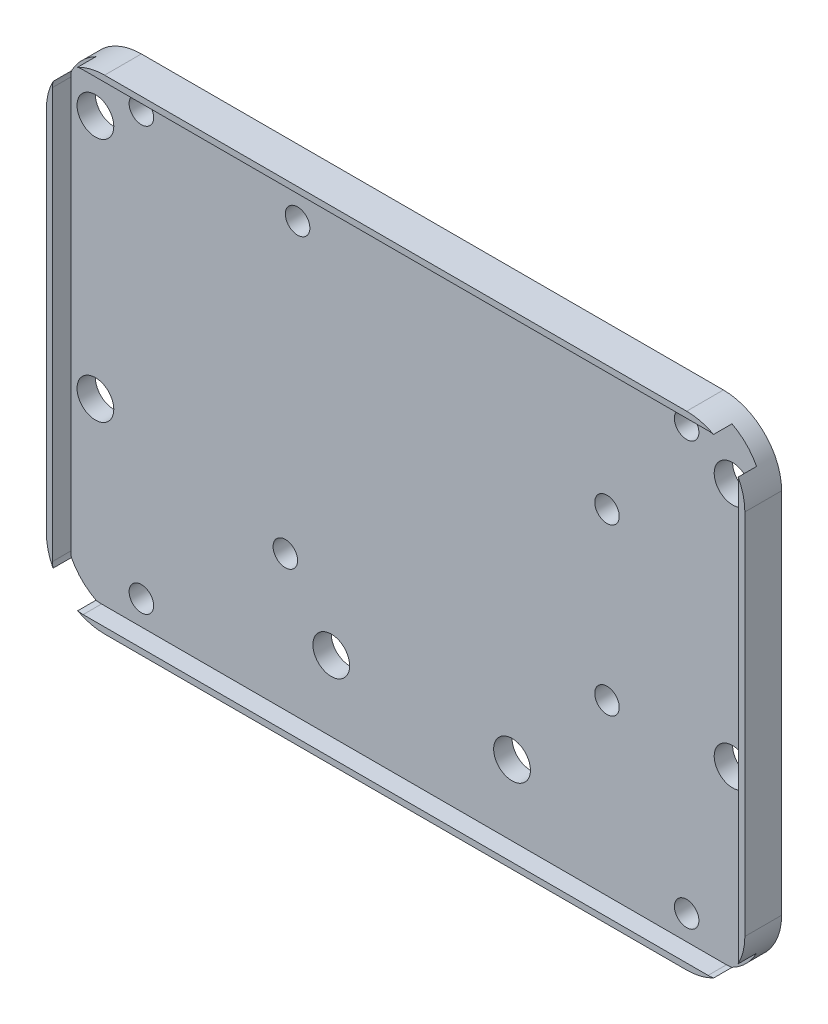
SolidWorks part; units mm, degrees
ref_plane "Plan de face" through (0, 0, 0) normal (0, 0, 1) x (1, 0, 0)
ref_plane "Plan de dessus" through (0, 0, 0) normal (0, 1, 0) x (1, 0, 0)
ref_plane "Plan de droite" through (0, 0, 0) normal (1, 0, 0) x (0, 0, -1)
sketch "Esquisse1" plane through (0, 0, 0) normal (0, 0, 1) x (1, 0, 0)
  line L1 (7.9933, 75.3455) -> (102.9933, 75.3455)
  line L2 (-1.5067, 65.8455) -> (-1.5067, 5.8455)
  line L3 (7.9933, -3.6545) -> (102.9933, -3.6545)
  line L4 (112.4933, 65.8455) -> (112.4933, 5.8455)
  circle A0 centre (107.4933, 65.8455) radius 3
  circle A1 centre (107.4933, 25.8455) radius 3
  circle A2 centre (3.4933, 65.8455) radius 3
  circle A3 centre (3.4933, 25.8455) radius 3
  arc A4 (-1.5067, 5.8455) -> (7.9933, -3.6545) centre (7.9933, 5.8455) ccw
  arc A5 (102.9933, -3.6545) -> (112.4933, 5.8455) centre (102.9933, 5.8455) ccw
  arc A6 (102.9933, 75.3455) -> (112.4933, 65.8455) centre (102.9933, 65.8455) cw
  arc A7 (7.9933, 75.3455) -> (-1.5067, 65.8455) centre (7.9933, 65.8455) ccw
  point P18 (112.4933, 75.3455)
  point P21 (-1.5067, 75.3455)
  dimension "D1" = 40
  dimension "D4" = 40
  dimension "D8" = 6
  dimension "D9" = 6
  dimension "D10" = 6
  dimension "D11" = 6
  dimension "D2" = 79
  dimension "D3" = 114
  dimension "D5" = 104
  dimension "D6" = 104
  dimension "D7" = 5
  dimension "D12" = 9.5
extrude "Boss.-Extru.3" add sketch "Esquisse1" along normal blind 6
sketch "Esquisse3" plane through (0, 0, 6) normal (0, 0, 1) x (1, 0, 0)
  line L0 (-1.5067, 65.8455) -> (-1.5067, 5.8455) construction
  line L1 (4.4933, 74.3455) -> (106.4933, 74.3455)
  line L2 (-0.5067, 69.3455) -> (-0.5067, 2.3455)
  line L3 (4.4933, -2.6545) -> (106.4933, -2.6545)
  line L4 (111.4933, 69.3455) -> (111.4933, 2.3455)
  line L5 (102.9933, 75.3455) -> (7.9933, 75.3455) construction
  line L6 (7.9933, -3.6545) -> (102.9933, -3.6545) construction
  line L7 (112.4933, 5.8455) -> (112.4933, 65.8455) construction
  arc A0 (-0.5067, 2.3455) -> (4.4933, -2.6545) centre (4.4933, 2.3455) ccw
  arc A1 (106.4933, -2.6545) -> (111.4933, 2.3455) centre (106.4933, 2.3455) ccw
  arc A2 (106.4933, 74.3455) -> (111.4933, 69.3455) centre (106.4933, 69.3455) cw
  arc A3 (4.4933, 74.3455) -> (-0.5067, 69.3455) centre (4.4933, 69.3455) ccw
  point P12 (0, 0)
  dimension "D5" = 5
  dimension "D1" = 1
  dimension "D2" = 1
  dimension "D3" = 1
  dimension "D4" = 1
extrude "Enlèv. mat.-Extru.2" cut sketch "Esquisse3" against normal blind 3
sketch "Esquisse5" plane through (0, 0, 3) normal (0, 0, 1) x (1, 0, 0)
  line L0 (-1.5067, 65.8455) -> (-1.5067, 5.8455) construction
  line L1 (102.9933, 75.3455) -> (7.9933, 75.3455) construction
  line L3 (7.9933, -3.6545) -> (102.9933, -3.6545) construction
  line L15 (4.4933, -2.6545) -> (106.4933, -2.6545) construction
  circle A0 centre (10.9933, 70.3455) radius 2
  circle A1 centre (99.9933, 70.3455) radius 2
  circle A2 centre (10.9933, 1.3455) radius 2
  circle A3 centre (99.9933, 1.3455) radius 2
  circle A4 centre (41.9933, 8.8455) radius 3
  circle A5 centre (71.4933, 8.8455) radius 3
  circle A6 centre (36.4933, 67.473) radius 2
  circle A7 centre (34.4933, 19.473) radius 2
  circle A8 centre (86.9933, 51.973) radius 2
  circle A9 centre (86.9933, 24.973) radius 2
  point P18 (0, 0)
  point P19 (0, 0)
  point P34 (0, 0)
  point P37 (0, 0)
  point P38 (83.9933, 71.7212)
  dimension "D1" = 89
  dimension "D5" = 5
  dimension "D9" = 29.5
  dimension "D2" = 12.5
  dimension "D3" = 5
  dimension "D4" = 5
  dimension "D6" = 89
  dimension "D7" = 12.5
  dimension "D8" = 69
  dimension "D10" = 11.5
extrude "Enlèv. mat.-Extru.3" cut sketch "Esquisse5" against normal blind 3
